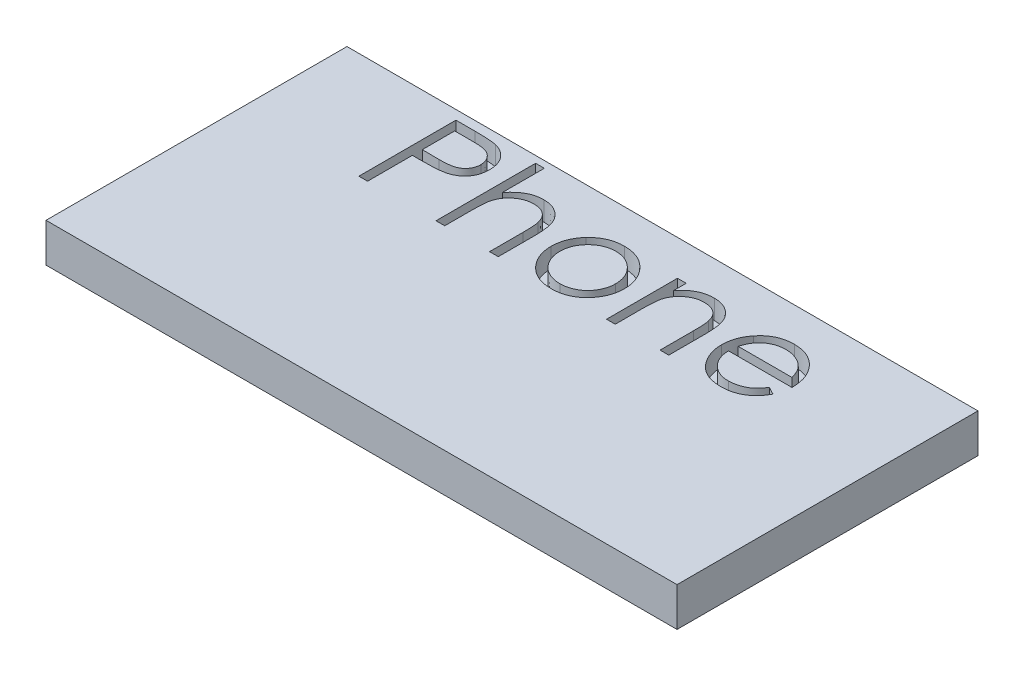
SolidWorks part; units mm, degrees
ref_plane "Front Plane" through (0, 0, 0) normal (0, 0, 1) x (1, 0, 0)
ref_plane "Top Plane" through (0, 0, 0) normal (0, 1, 0) x (1, 0, 0)
ref_plane "Right Plane" through (0, 0, 0) normal (1, 0, 0) x (0, 0, -1)
other "Center of Mass"
sketch "Sketch1" plane through (0, 0, 0) normal (0, 1, 0) x (1, 0, 0)
  line L1 (0, 0) -> (165.1, 0)
  line L2 (0, 0) -> (0, 78.74)
  line L3 (0, 78.74) -> (165.1, 78.74)
  line L4 (165.1, 0) -> (165.1, 78.74)
  dimension "D1" = 165.1
  dimension "D2" = 78.74
extrude "Boss-Extrude1" add sketch "Sketch1" along normal blind 10.16 contours L3 L4 L1 L2
sketch "Sketch2" plane through (0, 10.16, 0) normal (0, 1, 0) x (1, 0, 0)
  line L0 (0, 50.915) -> (165.1, 50.915) construction
  line L1 (0, 0) -> (0, 78.74) construction
  line L2 (165.1, 0) -> (165.1, 78.74) construction
  text T0 "Phone" font "Century Gothic" height 25.4
extrude "Cut-Extrude1" cut sketch "Sketch2" against normal blind 5.08
